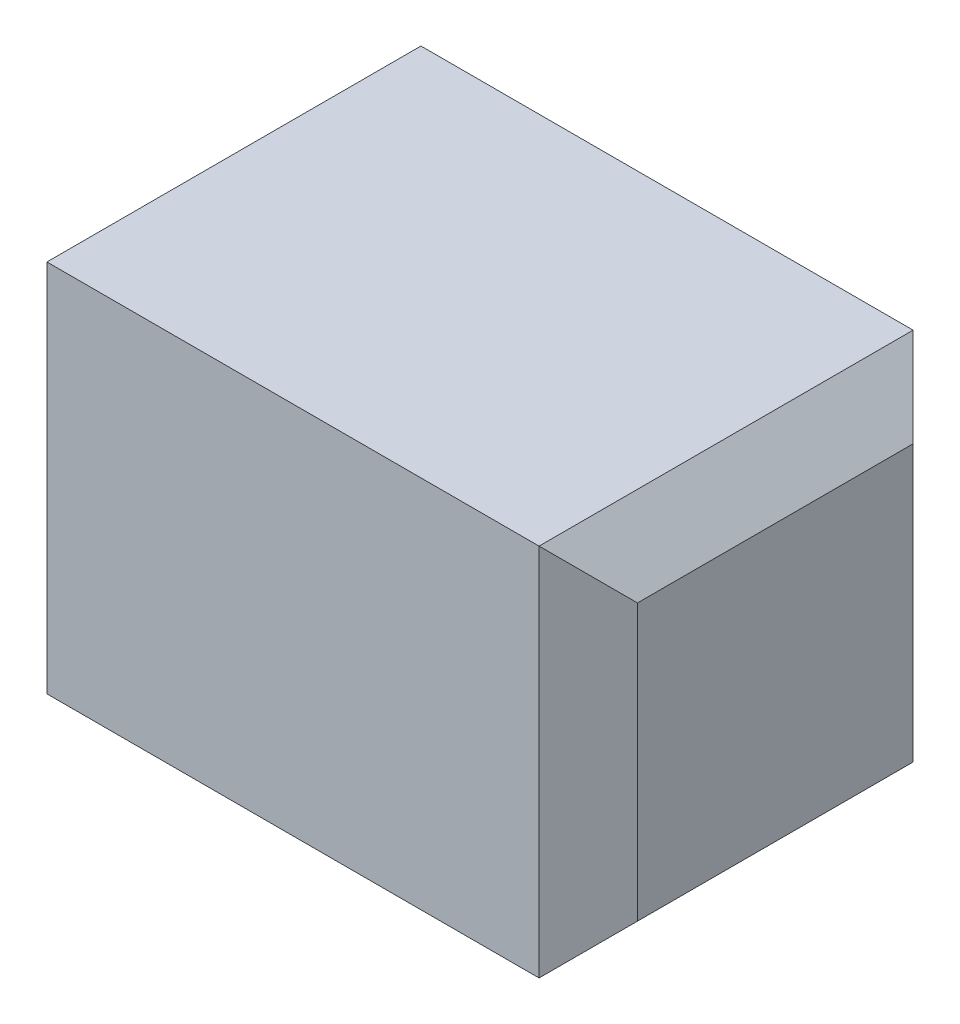
SolidWorks part; units mm, degrees
ref_plane "Front Plane" through (0, 0, 0) normal (0, 0, 1) x (1, 0, 0)
ref_plane "Top Plane" through (0, 0, 0) normal (0, 1, 0) x (1, 0, 0)
ref_plane "Right Plane" through (0, 0, 0) normal (1, 0, 0) x (0, 0, -1)
sketch "Sketch1" plane through (0, 0, 0) normal (0, 1, 0) x (1, 0, 0)
  line L1 (-3, 1.9) -> (3, 1.9)
  line L2 (-3, 1.9) -> (-3, -1.9)
  line L3 (-3, -1.9) -> (3, -1.9)
  line L4 (3, 1.9) -> (3, -1.9)
  line L5 (-3, 1.9) -> (3, -1.9) construction
  line L6 (-3, -1.9) -> (3, 1.9) construction
  point P0 (0, 0)
  dimension "D1" = 6
  dimension "D2" = 3.8
extrude "Boss-Extrude1" add sketch "Sketch1" along normal blind 3.8
chamfer "Chamfer1" distance 0.5 angle 45 8 edges at (-3, 1.9, -1.9) (-3, 3.8, 0) (-3, 1.9, 1.9) (-3, 0, 0) (3, 1.9, 1.9) (3, 3.8, 0) (3, 1.9, -1.9) (3, 0, 0)
